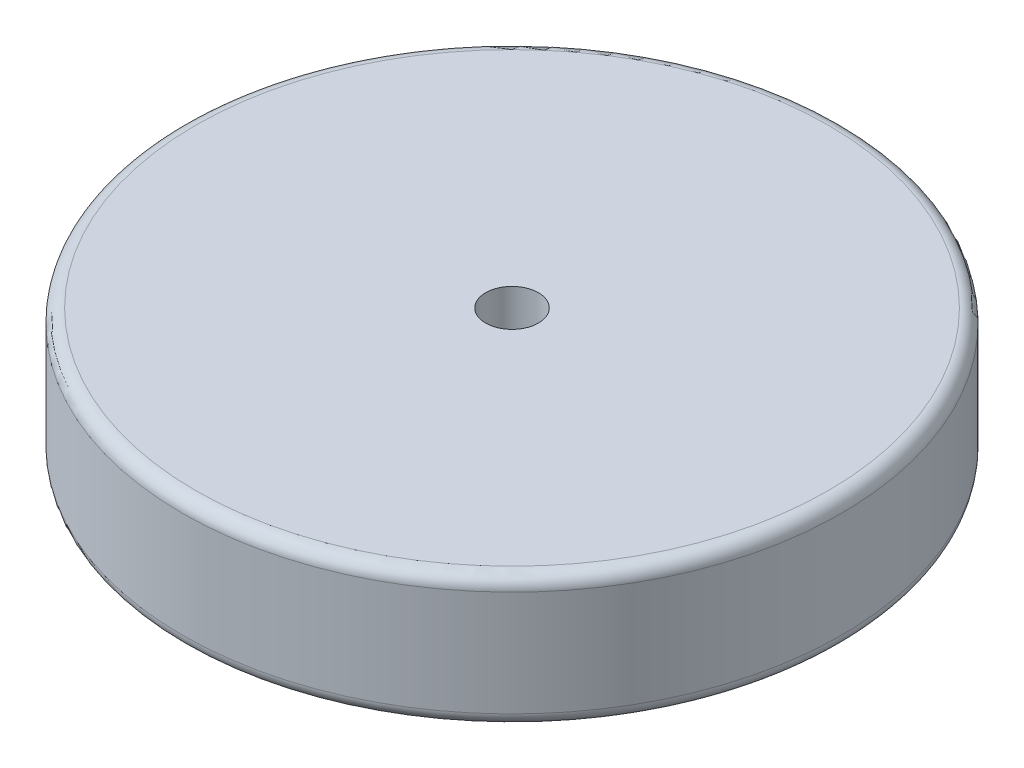
SolidWorks part; units mm, degrees
ref_plane "Front Plane" through (0, 0, 0) normal (0, 0, 1) x (1, 0, 0)
ref_plane "Top Plane" through (0, 0, 0) normal (0, 1, 0) x (1, 0, 0)
ref_plane "Right Plane" through (0, 0, 0) normal (1, 0, 0) x (0, 0, -1)
sketch "Sketch1" plane through (0, 0, 0) normal (0, 1, 0) x (1, 0, 0)
  circle A0 centre (0, 0) radius 25
  circle A1 centre (0, 0) radius 2
  point P2 (0, 0)
  dimension "D1" = 50
  dimension "D2" = 4
extrude "Boss-Extrude1" add sketch "Sketch1" along normal blind 10
fillet "Fillet1" radius 1 2 edges at (0, 0, 25) (0, 10, 25)
